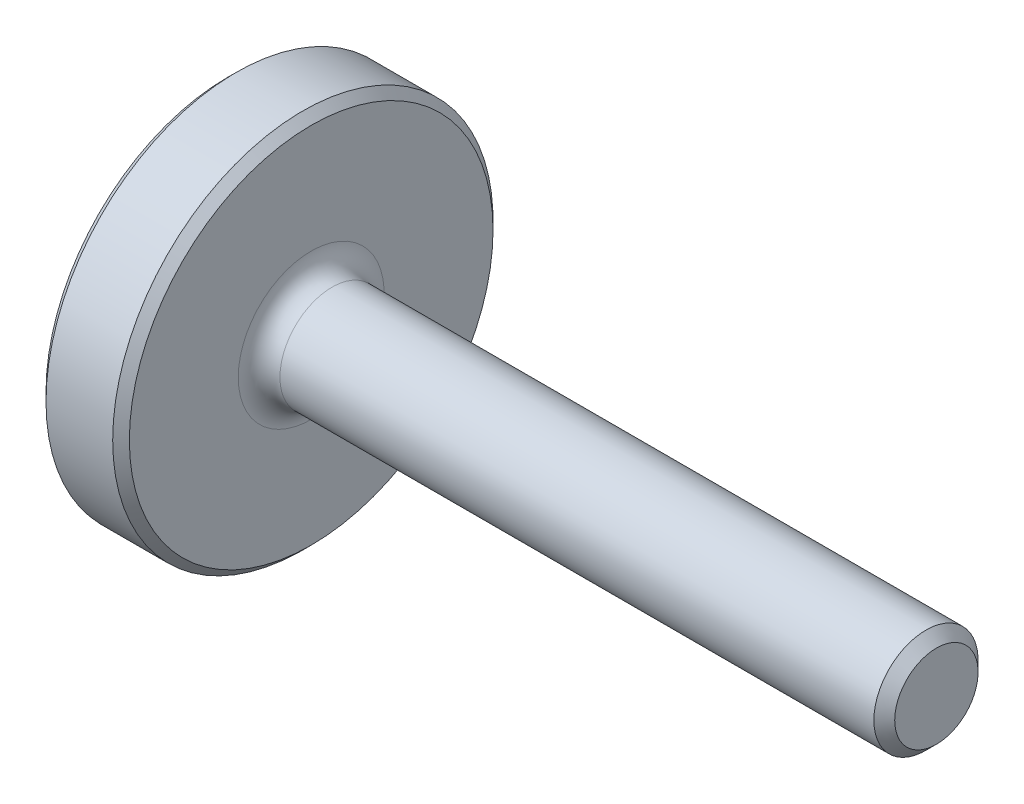
SolidWorks part; units mm, degrees
revolve "Base-Revolve" add sketch "BodySke"
sketch "BodySke" plane through (0, 0, 0) normal (0, 0, 1) x (1, 0, 0)
  line L0 (67, 5) -> (68, 4)
  line L1 (0, 0) -> (0, 17.45)
  line L2 (-11.4008, 0) -> (80.9761, 0) construction
  line L3 (68, 0) -> (0, 0)
  line L5 (68, 4) -> (68, 0)
  line L6 (0.8, 18.25) -> (7.2, 18.25)
  line L7 (4, 31.75) -> (4, -6.35) construction
  line L8 (0.8, 18.25) -> (0, 17.45)
  line L9 (10, 6.5875) -> (10, -2.9375) construction
  line L10 (18, 6.35) -> (18, -3.175) construction
  line L11 (7.2, 18.25) -> (8, 17.45)
  line L14 (8, 5) -> (67, 5)
  line L15 (8, 5) -> (8, 17.45)
  point P9 (68, 5)
  dimension "D1" = 45
  dimension "Chamfer" = 0.8
  dimension "Thread_nom" = 50
  dimension "Length" = 60
  dimension "Head_ht" = 8
  dimension "Advance" = 2
  dimension "D4" = 45
  dimension "Head_dia" = 36.5
  dimension "Diameter" = 10
  dimension "Minor_dia" = 8
cosmetic thread "ThreadCosmetic" [suppressed]
fillet "Fillet2" radius 2 1 edges at (8, 0, 5)
ref_plane "Plane1" through (0, 0, 0) normal (0, 0, 1) x (1, 0, 0)
ref_plane "Plane2" through (0, 0, 0) normal (0, 1, 0) x (1, 0, 0)
ref_plane "Plane3" through (0, 0, 0) normal (1, 0, 0) x (0, 0, -1)
sketch "UcutSke" plane through (0, 0, 0) normal (0, 0, 1) x (1, 0, 0)
  line L0 (14, 5) -> (14, 4.5)
  line L1 (14.5, 4) -> (15.134, 4)
  line L2 (15.384, 4.067) -> (17, 5)
  line L3 (-5.0411, 0) -> (27.7823, 0) construction
  line L5 (14, 5) -> (17, 5)
  line L6 (8, -17.45) -> (8, 17.45) construction
  arc A0 (14.5, 4) -> (14, 4.5) centre (14.5, 4.5) cw
  arc A1 (15.384, 4.067) -> (15.134, 4) centre (15.134, 4.5) cw
  dimension "Diameter" = 10
  dimension "D2" = 30
revolve "UnderCut" [suppressed] cut sketch "UcutSke" angle 360 about L3
sketch "ThdSchSke" plane through (0, 0, 0) normal (0, 0, 1) x (1, 0, 0)
  line L0 (17, -4) -> (16.2998, -5)
  line L1 (17, -4) -> (17.7002, -5)
  line L2 (17.7002, -5) -> (17.7002, -6.25)
  line L3 (-3.175, 0) -> (5.1513, 0) construction
  line L5 (17.7002, -6.25) -> (16.2998, -6.25)
  line L6 (16.2998, -6.25) -> (16.2998, -5)
  line L8 (8, -17.45) -> (8, 17.45) construction
  dimension "Thread_minor" = 8
  dimension "Diameter" = 10
  dimension "Start" = 9
revolve "ThreadSchematic" [suppressed] cut sketch "ThdSchSke" angle 360 about L3
pattern_linear "ThdSchPat" [suppressed]
sketch "KnurlSke" plane through (0, 0, 0) normal (-1, 0, 0) x (0, 0, 1)
  line L0 (0, 17.65) -> (0, 3.175) construction
  line L1 (0, 17.65) -> (0.3445, 18.2467)
  line L2 (0, 17.65) -> (-0.3445, 18.2467)
  line L3 (0, 18.25) -> (0, 17.65) construction
  circle A0 centre (0, 0) radius 18.25 construction
  arc A1 (0.3445, 18.2467) -> (-0.3445, 18.2467) centre (0, 0) ccw
extrude "Knurl_cut" [suppressed] cut sketch "KnurlSke" against normal up to next
pattern_circular "Knurl" [suppressed] count 86 over 360
sketch "Sketch1" plane through (68, 0, 0) normal (1, 0, 0) x (0, 0, -1)
  circle A0 centre (0, 0) radius 0.5
  dimension "D1" = 1
extrude "Nothing" add sketch "Sketch1" against normal blind 2
equation "\"Thread_minor@ThreadCosmetic\" = \"Minor_dia@BodySke\""
equation "\"Thread_minor@ThdSchSke\" = \"Thread_minor@ThreadCosmetic\""
equation "\"Diameter@ThdSchSke\" = \"Diameter@BodySke\""
equation "\"Overcut@ThdSchSke\" = \"Diameter@BodySke\" * 1.25"
equation "\"Start@ThdSchSke\" = \"e@UcutSke\" + \"Neck@UcutSke\""
equation "\"Thread_length@ThreadCosmetic\" = \"Length@BodySke\" - \"Start@ThdSchSke\""
equation "\"Num_threads@ThdSchPat\" = int( \"Thread_length@ThreadCosmetic\" / \"Advance@BodySke\" + 0.999 )  + 1"
equation "\"Advance@ThdSchPat\" = \"Thread_length@ThreadCosmetic\" /  (\"Num_threads@ThdSchPat\" - 1) 'relax it"
equation "\"Depth@KnurlSke\" = \"Chamfer@BodySke\" * 0.75"
equation "\"Count@Knurl\" =  ( 3.141592654 / 2 * \"Head_dia@BodySke\" )  / \"Depth@KnurlSke\" * 0.9"
equation "\"Minor@UcutSke\" = \"Minor_dia@BodySke\""
equation "\"Diameter@UcutSke\" = \"Diameter@BodySke\""
